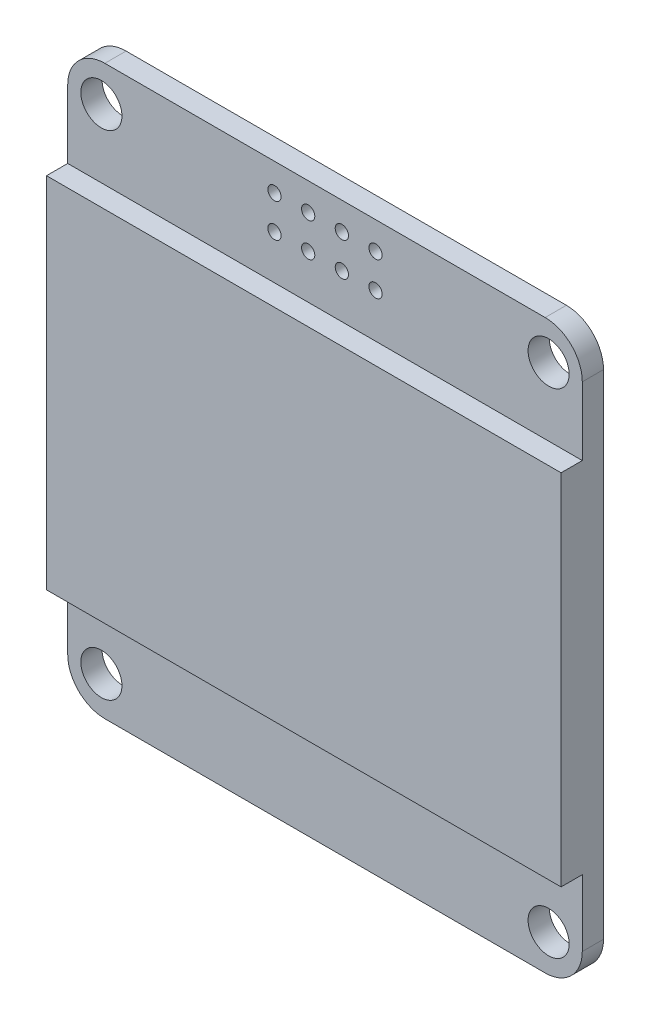
SolidWorks part; units mm, degrees
ref_plane "Ebene vorne" through (0, 0, 0) normal (0, 0, 1) x (1, 0, 0)
ref_plane "Ebene oben" through (0, 0, 0) normal (0, 1, 0) x (1, 0, 0)
ref_plane "Ebene rechts" through (0, 0, 0) normal (1, 0, 0) x (0, 0, -1)
sketch "Skizze1" plane through (0, 0, 0) normal (0, 0, 1) x (1, 0, 0)
  line L0 (-16.8617, 18.6) -> (16.8617, 18.6) construction
  line L1 (16.6, -21.4) -> (-16.6, -21.4)
  line L2 (19.4, -18.6) -> (19.4, 18.6)
  line L3 (16.6, 21.4) -> (-16.6, 21.4)
  line L4 (-19.4, -18.6) -> (-19.4, 18.6)
  line L5 (19.4, -21.4) -> (-19.4, 21.4) construction
  line L6 (19.4, 21.4) -> (-19.4, -21.4) construction
  line L7 (16.8617, 18.6) -> (16.8617, -18.6) construction
  line L8 (16.8617, -18.6) -> (-16.8617, -18.6) construction
  line L9 (-16.8617, -18.6) -> (-16.8617, 18.6) construction
  circle A0 centre (-16.8617, 18.6) radius 1.55
  circle A1 centre (-16.8617, -18.6) radius 1.55
  circle A2 centre (16.8617, -18.6) radius 1.55
  circle A3 centre (16.8617, 18.6) radius 1.55
  arc A4 (19.4, 18.6) -> (16.6, 21.4) centre (16.6, 18.6) ccw
  arc A5 (16.6, -21.4) -> (19.4, -18.6) centre (16.6, -18.6) ccw
  arc A6 (-16.6, -21.4) -> (-19.4, -18.6) centre (-16.6, -18.6) cw
  arc A7 (-16.6, 21.4) -> (-19.4, 18.6) centre (-16.6, 18.6) ccw
  point P0 (0, 0)
  dimension "D3" = 3.1
  dimension "D4" = 3.1
  dimension "D5" = 3.1
  dimension "D6" = 3.1
  dimension "D8" = 2.8
  dimension "D1" = 42.8
  dimension "D2" = 38.8
  dimension "D7" = 37.2
extrude "Aufsatz-Linear austragen1" add sketch "Skizze1" along normal blind 1.6
sketch "Skizze2" plane through (0, 0, 1.6) normal (0, 0, 1) x (1, 0, 0)
  line L0 (-3.81, 19.3225) -> (3.81, 19.3225) construction
  line L1 (3.81, 19.3225) -> (3.81, 16.7825) construction
  line L2 (3.81, 16.7825) -> (-3.81, 16.7825) construction
  line L3 (-3.81, 16.7825) -> (-3.81, 19.3225) construction
  line L4 (0, 19.3225) -> (0, 21.4) construction
  line L5 (16.6, 21.4) -> (-16.6, 21.4) construction
  line L6 (-16.8617, 18.6) -> (16.8617, 18.6) construction
  circle A0 centre (-3.81, 16.7825) radius 0.5
  circle A1 centre (-1.27, 16.7825) radius 0.5
  circle A2 centre (1.27, 16.7825) radius 0.5
  circle A3 centre (3.81, 16.7825) radius 0.5
  circle A4 centre (-1.27, 19.3225) radius 0.5
  circle A5 centre (1.27, 19.3225) radius 0.5
  circle A6 centre (3.81, 19.3225) radius 0.5
  circle A7 centre (-3.81, 19.3225) radius 0.5
  point P24 (3.81, 19.3225)
  dimension "D1" = 1
  dimension "D4" = 2.54
  dimension "D5" = 2.54
  dimension "D2" = 4
  dimension "D3" = 2
extrude "Schnitt-Linear austragen1" cut sketch "Skizze2" against normal blind 1.6
sketch "Skizze3" plane through (0, 0, 1.6) normal (0, 0, 1) x (1, 0, 0)
  line L0 (-19.4, 18.6) -> (-19.4, -18.6) construction
  line L1 (-19.4, 13.4608) -> (19.4, 13.4608)
  line L2 (-19.4, 13.4608) -> (-19.4, -13.583)
  line L3 (-19.4, -13.583) -> (19.4, -13.583)
  line L4 (19.4, 13.4608) -> (19.4, -13.583)
  line L5 (19.4, -18.6) -> (19.4, 18.6) construction
extrude "Aufsatz-Linear austragen2" add sketch "Skizze3" along normal blind 1.6
sketch "Skizze4" plane through (0, 0, 0) normal (0, 0, -1) x (-1, 0, 0)
  line L1 (8.3697, 7.6366) -> (12.239, 7.6366)
  line L2 (8.3697, 7.6366) -> (8.3697, -6.374)
  line L3 (8.3697, -6.374) -> (12.239, -6.374)
  line L4 (12.239, 7.6366) -> (12.239, -6.374)
extrude "Aufsatz-Linear austragen3" add sketch "Skizze4" along normal blind 2
equation "\"D4@Skizze1\"=\"D3@Skizze1\""
equation "\"D5@Skizze1\"=\"D3@Skizze1\""
equation "\"D6@Skizze1\"=\"D3@Skizze1\""
